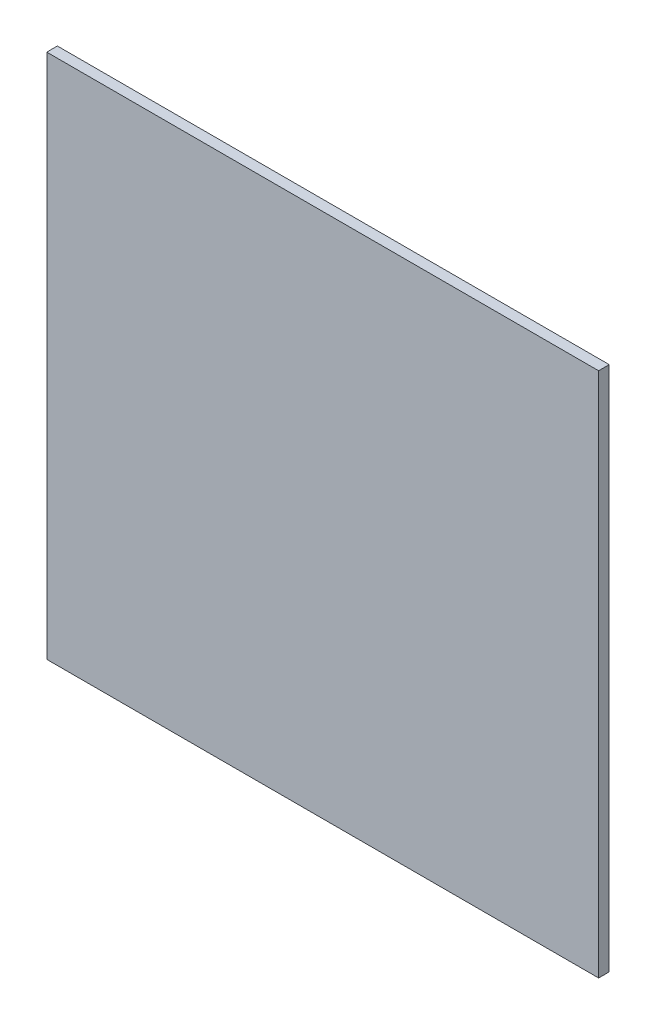
SolidWorks part; units mm, degrees
ref_plane "Plan de face" through (0, 0, 0) normal (0, 0, 1) x (1, 0, 0)
ref_plane "Plan de dessus" through (0, 0, 0) normal (0, 1, 0) x (1, 0, 0)
ref_plane "Plan de droite" through (0, 0, 0) normal (1, 0, 0) x (0, 0, -1)
sketch "Esquisse1" plane through (0, 0, 0) normal (0, 0, 1) x (1, 0, 0)
  line L1 (-78, -79.6218) -> (78, -79.6218)
  line L2 (-78, -79.6218) -> (-78, 69.0382)
  line L3 (-78, 69.0382) -> (78, 69.0382)
  line L4 (78, -79.6218) -> (78, 69.0382)
  point P0 (0, 0)
  dimension "D1" = 156
  dimension "D2" = 148.66
extrude "Boss.-Extru.1" add sketch "Esquisse1" along normal blind 3
